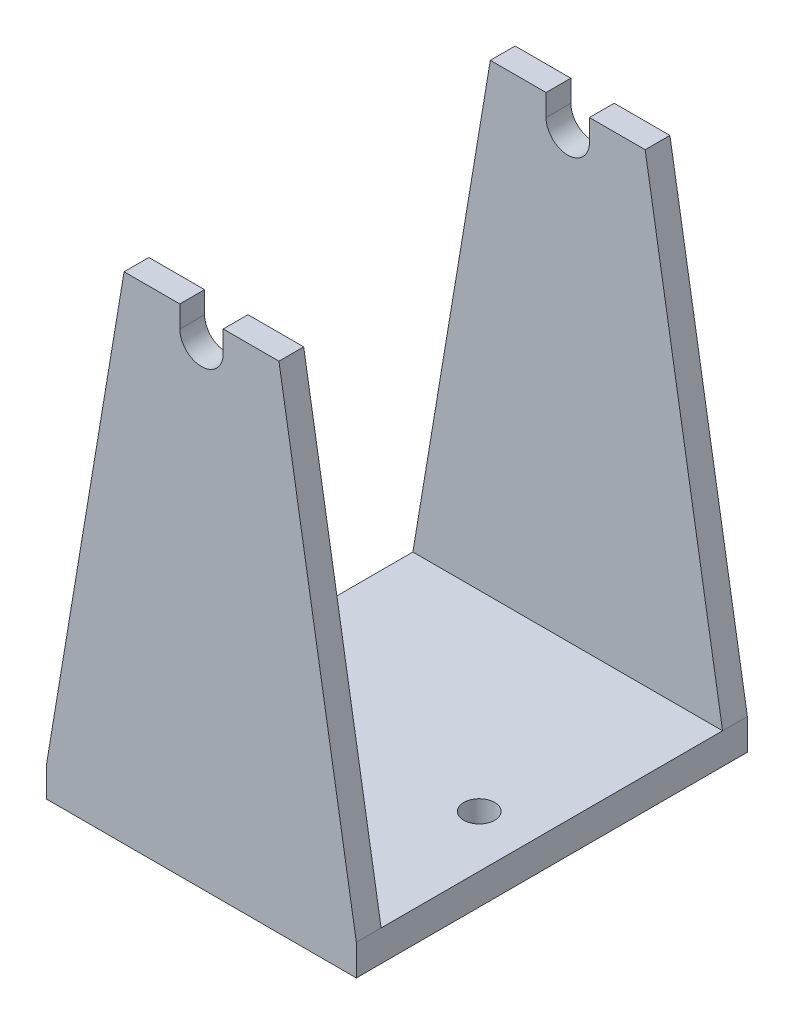
SolidWorks part; units mm, degrees
ref_plane "Piano frontale" through (0, 0, 0) normal (0, 0, 1) x (1, 0, 0)
ref_plane "Piano superiore" through (0, 0, 0) normal (0, 1, 0) x (1, 0, 0)
ref_plane "Piano destro" through (0, 0, 0) normal (1, 0, 0) x (0, 0, -1)
sketch "Schizzo1" plane through (0, 0, 0) normal (0, 0, 1) x (1, 0, 0)
  line L0 (0, 73) -> (0, 0) construction
  line L1 (-25, 0) -> (25, 0)
  line L2 (25, 0) -> (25, 5)
  line L3 (25, 5) -> (12.5, 80)
  line L4 (12.5, 80) -> (3.5, 80)
  line L5 (-12.5, 80) -> (-3.5, 80)
  line L6 (-25, 5) -> (-12.5, 80)
  line L7 (-25, 0) -> (-25, 5)
  line L11 (3.5, 76.5) -> (3.5, 80)
  line L12 (-3.5, 76.5) -> (-3.5, 80)
  arc A0 (3.5, 76.5) -> (-3.5, 76.5) centre (0, 76.5) cw
  dimension "D2" = 3.5
  dimension "D6" = 3.5
  dimension "D1" = 50
  dimension "D3" = 25
  dimension "D4" = 5
  dimension "D5" = 80
extrude "Estrusione-Estrusione1" add sketch "Schizzo1" along normal blind 4
sketch "Schizzo2" plane through (0, 0, 4) normal (0, 0, 1) x (1, 0, 0)
  line L1 (-25, 5) -> (25, 5)
  line L2 (-25, 5) -> (-25, 0)
  line L3 (-25, 0) -> (25, 0)
  line L4 (25, 5) -> (25, 0)
extrude "Estrusione-Estrusione2" add sketch "Schizzo2" along normal blind 55.13
sketch "Schizzo3" plane through (0, 0, 59.13) normal (0, 0, 1) x (1, 0, 0)
  line L9 (3.5, 80) -> (3.5, 76.5)
  line L10 (12.5, 80) -> (3.5, 80)
  line L11 (25, 5) -> (12.5, 80)
  line L12 (25, 0) -> (25, 5)
  line L13 (-25, 0) -> (25, 0)
  line L14 (-25, 5) -> (-25, 0)
  line L15 (-12.5, 80) -> (-25, 5)
  line L16 (-3.5, 80) -> (-12.5, 80)
  line L17 (-3.5, 76.5) -> (-3.5, 80)
  line L18 (3.5, 80) -> (3.5, 76.5)
  line L19 (12.5, 80) -> (3.5, 80)
  line L20 (25, 5) -> (12.5, 80)
  line L21 (25, 0) -> (25, 5)
  line L22 (-25, 0) -> (25, 0)
  line L23 (-25, 5) -> (-25, 0)
  line L24 (-12.5, 80) -> (-25, 5)
  line L25 (-3.5, 80) -> (-12.5, 80)
  line L26 (-3.5, 76.5) -> (-3.5, 80)
  arc A1 (-3.5, 76.5) -> (3.5, 76.5) centre (0, 76.5) ccw
  arc A2 (-3.5, 76.5) -> (3.5, 76.5) centre (0, 76.5) ccw
  dimension "D1" = 0
extrude "Estrusione-Estrusione3" add sketch "Schizzo3" along normal blind 4
hole_wizard "Foro per Vite M5-1" positions "Schizzo4" profile "Schizzo5" hole size "M5" standard "Ansi Metric" end condition through all
sketch "Schizzo4" plane through (658.3889, -5, 71.0183) normal (0, -1, 0) x (-0.2837, 0, -0.9589)
  point P1 (223.7869, -629.1294)
  point P4 (216.6945, -605.1565)
sketch "Schizzo5" plane through (-8.3798, -5, 34.9084) normal (1, 0, 0) x (0, 0, -1)
  line L0 (0, 0) -> (0, 85)
  line L1 (0, 85) -> (2.5, 85)
  line L2 (2.5, 85) -> (2.5, 0)
  line L3 (2.5, 0) -> (0, 0)
  line L4 (0, -6.35) -> (0, 107.95) construction
  dimension "Thru Hole Dia." = 5
  dimension "Thru Hole Depth" = 85
